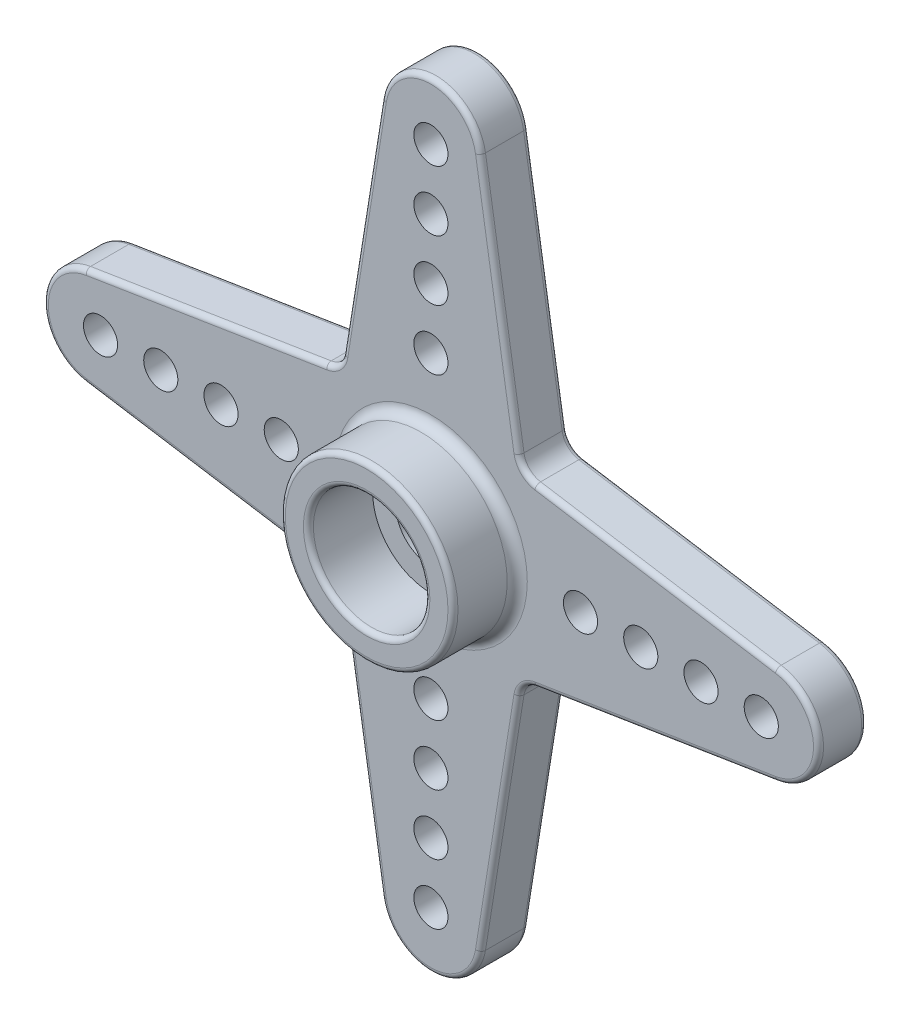
SolidWorks part; units mm, degrees
ref_plane "Front Plane" through (0, 0, 0) normal (0, 0, 1) x (1, 0, 0)
ref_plane "Top Plane" through (0, 0, 0) normal (0, 1, 0) x (1, 0, 0)
ref_plane "Right Plane" through (0, 0, 0) normal (1, 0, 0) x (0, 0, -1)
sketch "Sketch1" plane through (0, 0, 0) normal (0, 0, 1) x (1, 0, 0)
  line L0 (-4.5, 4.5) -> (-17.195, 2.4686)
  line L1 (-17.195, -2.4686) -> (-4.5, -4.5)
  line L2 (0, 16.8) -> (0, -16.8) construction
  line L3 (16.8, 0) -> (-16.8, 0) construction
  line L4 (17.195, -2.4686) -> (4.5, -4.5)
  line L5 (4.5, 4.5) -> (17.195, 2.4686)
  line L6 (4.5, 4.5) -> (2.4686, 17.195)
  line L7 (-2.4686, 17.195) -> (-4.5, 4.5)
  line L8 (-2.4686, -17.195) -> (-4.5, -4.5)
  line L9 (4.5, -4.5) -> (2.4686, -17.195)
  line L10 (4.5, 4.5) -> (4.5, -4.5) construction
  line L11 (4.5, 4.5) -> (-4.5, 4.5) construction
  arc A0 (2.4686, -17.195) -> (-2.4686, -17.195) centre (0, -16.8) cw
  circle A1 centre (0, 0) radius 1.75
  arc A2 (-17.195, 2.4686) -> (-17.195, -2.4686) centre (-16.8, 0) ccw
  arc A3 (17.195, 2.4686) -> (17.195, -2.4686) centre (16.8, 0) cw
  arc A5 (2.4686, 17.195) -> (-2.4686, 17.195) centre (0, 16.8) ccw
  dimension "D1" = 33.6
  dimension "D2" = 3.5
  dimension "D3" = 2.5
  dimension "D4" = 9
extrude "Boss-Extrude1" add sketch "Sketch1" along normal blind 2.4
sketch "Sketch2" plane through (0, 0, 2.4) normal (0, 0, 1) x (1, 0, 0)
  circle A0 centre (0, 0) radius 4.3
  circle A1 centre (0, 0) radius 2.9
  dimension "D1" = 8.6
  dimension "D2" = 5.8
extrude "Boss-Extrude2" add sketch "Sketch2" along normal blind 3.2
sketch "Sketch4" plane through (0, 0, 0) normal (0, 0, -1) x (-1, 0, 0)
  circle A0 centre (0, 0) radius 3.3
  circle A1 centre (0, 0) radius 3.6
  dimension "D1" = 7.2
  dimension "D2" = 6.6
extrude "Boss-Extrude3" add sketch "Sketch4" along normal blind 0.2
sketch "Sketch5" plane through (0, 0, 0) normal (0, 0, -1) x (-1, 0, 0)
  circle A0 centre (0, 0) radius 3.3 construction
  circle A1 centre (0, 0) radius 3.3
  circle A2 centre (0, 0) radius 4
  circle A3 centre (0, 0) radius 3.6 construction
  circle A4 centre (0, 0) radius 3.6
  dimension "D1" = 8
extrude "Cut-Extrude2" cut sketch "Sketch5" against normal blind 0.4
sketch "Sketch6" plane through (0, 0, 0) normal (0, 0, -1) x (-1, 0, 0)
  line L0 (0, 0) -> (0, 1.0197) construction
  circle A1 centre (7.45, 0) radius 0.85
  dimension "D1" = 1.7
  dimension "D2" = 7.45
extrude "Cut-Extrude3" cut sketch "Sketch6" against normal through all
pattern_linear "LPattern1" count 4 spacing 3 along (-1, 0, 0) of "Cut-Extrude3"
pattern_circular "CirPattern1" count 4 over 360 about axis through (0, 0, 0) along (0, 0, 1) of "Cut-Extrude3", "LPattern1"
fillet "Fillet3" radius 1 4 edges at (-4.5, -4.5, 1.2) (4.5, -4.5, 1.2) (4.5, 4.5, 1.2) (-4.5, 4.5, 1.2)
fillet "Fillet1" radius 0.25 34 edges at (4.3, 0, 5.6) (2.9, 0, 5.6) (-11.205, -3.4271, 2.4) (-19.3, 0, 2.4) (-11.205, 3.4271, 2.4) (11.205, 3.4271, 2.4) (19.3, 0, 2.4) (11.205, -3.4271, 2.4) (-11.205, -3.4271, 0) (-19.3, 0, 0) (-11.205, 3.4271, 0) (11.205, 3.4271, 0) (19.3, 0, 0) (11.205, -3.4271, 0) (-4.6659, 4.6659, 2.4) (-3.4271, 11.205, 2.4) (0, 19.3, 2.4) (3.4271, 11.205, 2.4) (4.6659, 4.6659, 2.4) (4.6659, -4.6659, 2.4) (3.4271, -11.205, 2.4) (0, -19.3, 2.4) (-3.4271, -11.205, 2.4) (-4.6659, -4.6659, 2.4) (-4.6659, 4.6659, 0) (-3.4271, 11.205, 0) (0, 19.3, 0) (3.4271, 11.205, 0) (4.6659, 4.6659, 0) (4.6659, -4.6659, 0) (3.4271, -11.205, 0) (0, -19.3, 0) (-3.4271, -11.205, 0) (-4.6659, -4.6659, 0)
fillet "Fillet2" radius 0.5 1 edges at (4.3, 0, 2.4)
